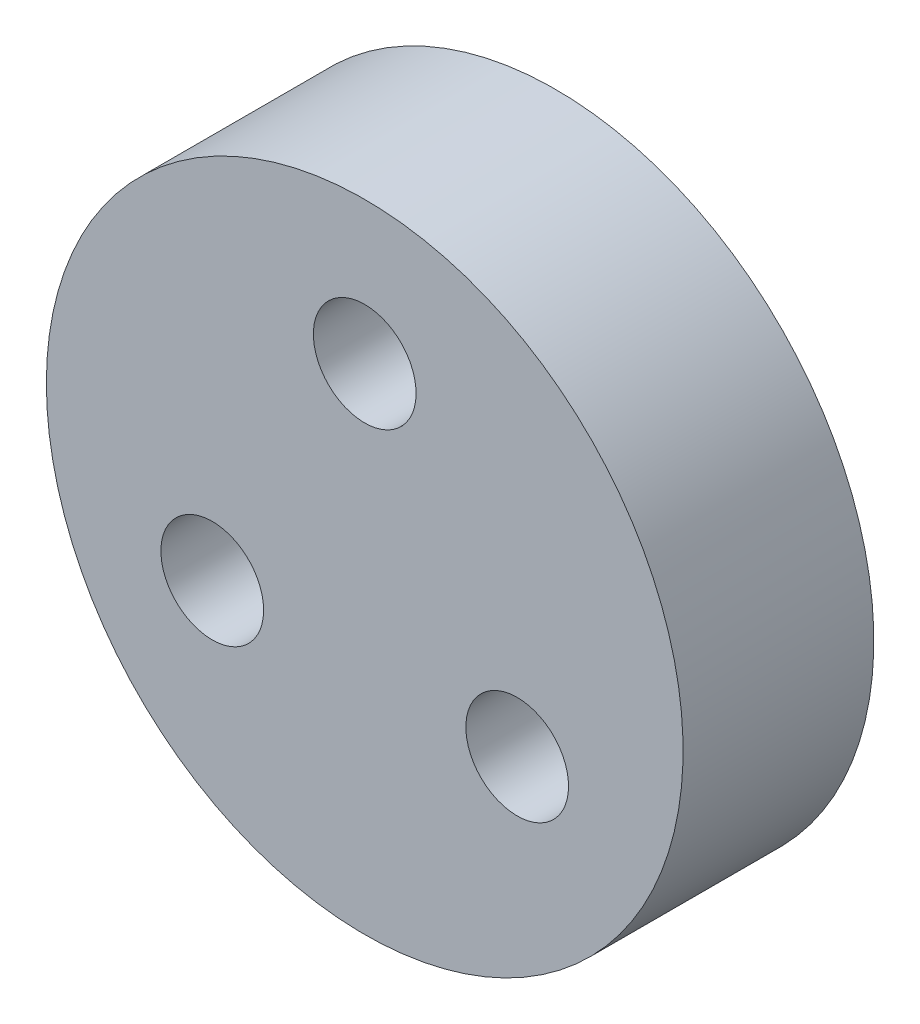
SolidWorks part; units mm, degrees
material "ABS"
ref_plane "Front Plane" through (0, 0, 0) normal (0, 0, 1) x (1, 0, 0)
ref_plane "Top Plane" through (0, 0, 0) normal (0, 1, 0) x (1, 0, 0)
ref_plane "Right Plane" through (0, 0, 0) normal (1, 0, 0) x (0, 0, -1)
sketch "Sketch1" plane through (0, 0, 0) normal (0, 0, 1) x (1, 0, 0)
  circle A0 centre (0, 0) radius 10.85
  dimension "D1" = 21.7
extrude "Boss-Extrude1" add sketch "Sketch1" along normal blind 6.5
sketch "Sketch2" plane through (0, 0, 6.5) normal (0, 0, 1) x (1, 0, 0)
  line L0 (0, 0) -> (0, 10.85) construction
  line L1 (0, 0) -> (-10.85, 0) construction
  circle A0 centre (0, 0) radius 10.85 construction
  circle A1 centre (0, 6) radius 1.75
  circle A3 centre (5.1962, -3) radius 1.75
  circle A4 centre (-5.1962, -3) radius 1.75
  dimension "D2" = 3.5
  dimension "D1" = 6
  dimension "D3" = 3
extrude "Cut-Extrude1" cut sketch "Sketch2" against normal through all
